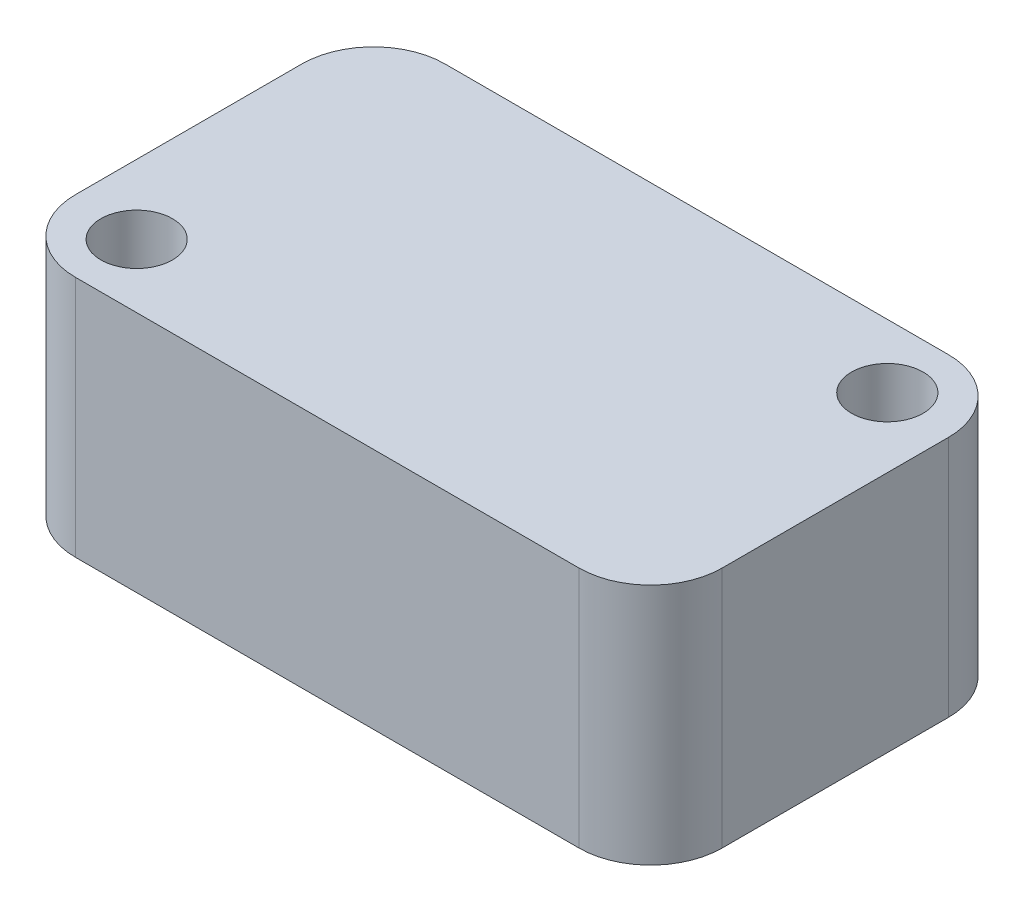
SolidWorks part; units mm, degrees
ref_plane "Front Plane" through (0, 0, 0) normal (0, 0, 1) x (1, 0, 0)
ref_plane "Top Plane" through (0, 0, 0) normal (0, 1, 0) x (1, 0, 0)
ref_plane "Right Plane" through (0, 0, 0) normal (1, 0, 0) x (0, 0, -1)
sketch "Sketch1" plane through (0, 0, 0) normal (0, 1, 0) x (1, 0, 0)
  line L0 (-1000, 0) -> (49000, 0) construction
  line L1 (-10.9, -8) -> (10.9, -8)
  line L2 (-14, -4.9) -> (-14, 4.9)
  line L3 (-10.9, 8) -> (10.9, 8)
  line L4 (14, -4.9) -> (14, 4.9)
  line L5 (-14, -8) -> (14, 8) construction
  line L6 (-14, 8) -> (14, -8) construction
  line L7 (-1000, 5.25) -> (49000, 5.25) construction
  line L8 (0, -1000) -> (0, 49000) construction
  arc A0 (14, 4.9) -> (10.9, 8) centre (10.9, 4.9) ccw
  arc A1 (10.9, -8) -> (14, -4.9) centre (10.9, -4.9) ccw
  arc A2 (-14, -4.9) -> (-10.9, -8) centre (-10.9, -4.9) ccw
  arc A3 (-14, 4.9) -> (-10.9, 8) centre (-10.9, 4.9) cw
  circle A4 centre (11, 5.25) radius 1.55
  circle A5 centre (-11, 5.25) radius 1.55 construction
  circle A6 centre (-11, -5.25) radius 1.55
  point P0 (0, 0)
  dimension "D3" = 3.1
  dimension "D5" = 3.1
  dimension "D1" = 16
  dimension "D2" = 28
  dimension "D6" = 11
  dimension "D4" = 5.25
extrude "Boss-Extrude1" add sketch "Sketch1" along normal blind 10.5
